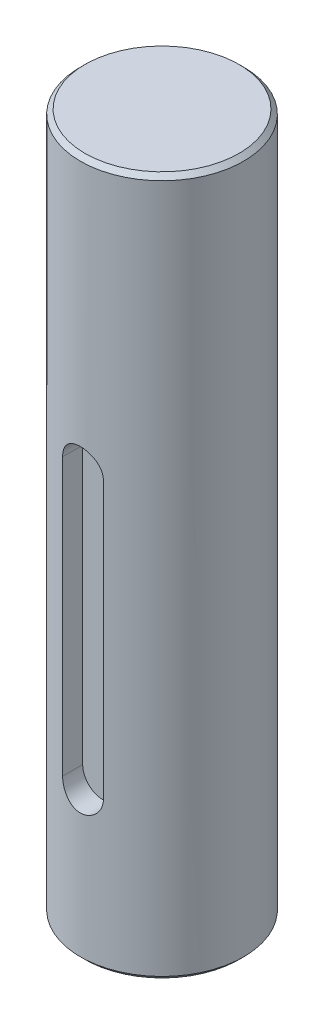
SolidWorks part; units mm, degrees
material "Acier allié inoxydable"
ref_plane "Plan de face" through (0, 0, 0) normal (0, 0, 1) x (1, 0, 0)
ref_plane "Plan de dessus" through (0, 0, 0) normal (0, 1, 0) x (1, 0, 0)
ref_plane "Plan de droite" through (0, 0, 0) normal (1, 0, 0) x (0, 0, -1)
sketch "Esquisse1" plane through (0, 0, 0) normal (0, 0, 1) x (1, 0, 0)
  line L0 (18, 154) -> (0, 154)
  line L1 (0, 154) -> (0, 0)
  line L2 (0, 0) -> (18, 0)
  line L3 (18, 0) -> (18, 154)
  line L4 (0, 154) -> (0, 0) construction
revolve "Révolution1" add sketch "Esquisse1" angle 360 about L4
ref_plane "Plan4" through (0, 0, 13) normal (0, 0, -1) x (-1, 0, 0)
sketch "Esquisse2" plane through (0, 0, 13) normal (0, 0, -1) x (-1, 0, 0)
  line L0 (-4.5, 94) -> (-4.5, 33)
  line L1 (4.5, 33) -> (4.5, 94)
  arc A0 (4.5, 94) -> (-4.5, 94) centre (0, 94) ccw
  arc A1 (-4.5, 33) -> (4.5, 33) centre (0, 33) ccw
extrude "Enlèv. mat.-Extru.1" cut sketch "Esquisse2" against normal up to next
chamfer "Chanfrein1" distance 1 angle 45 1 edges at (0, 154, -18)
chamfer "Chanfrein2" distance 1 angle 45 1 edges at (0, 0, -18)
